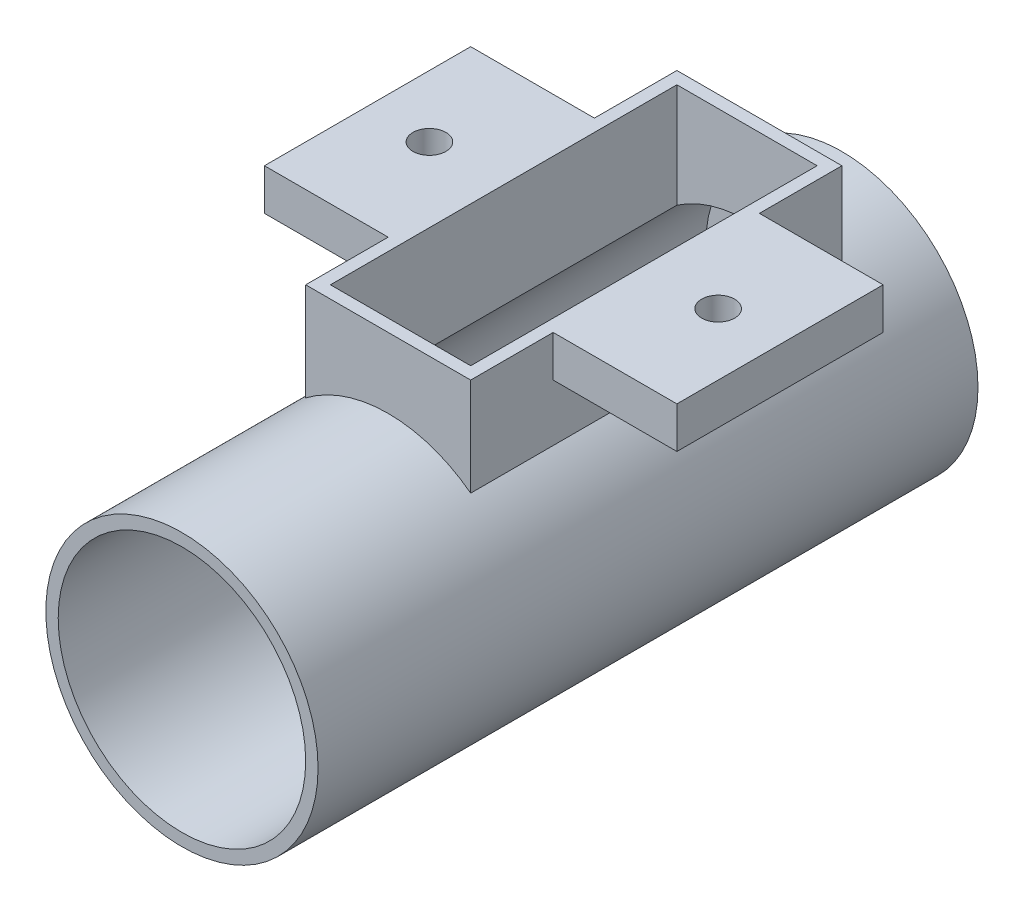
SolidWorks part; units mm, degrees
ref_plane "前视基准面" through (0, 0, 0) normal (0, 0, 1) x (1, 0, 0)
ref_plane "上视基准面" through (0, 0, 0) normal (0, 1, 0) x (1, 0, 0)
ref_plane "右视基准面" through (0, 0, 0) normal (1, 0, 0) x (0, 0, -1)
other "Configuration Table"
sketch "草图1" plane through (0, 0, 0) normal (0, 0, 1) x (1, 0, 0)
  circle A0 centre (0, 0) radius 33
  dimension "D1" = 66
extrude "凸台-拉伸1" add sketch "草图1" along normal blind 160
shell "抽壳1" thickness 3
ref_plane "基准面1" through (0, 33, 0) normal (0, 1, 0) x (1, 0, 0)
ref_plane "基准面2" through (0, 50, 0) normal (0, 1, 0) x (1, 0, 0)
sketch "草图2" plane through (0, 50, 0) normal (0, 1, 0) x (1, 0, 0)
  line L0 (0, 0) -> (0, -160) construction
  line L1 (-20, -20) -> (20, -20)
  line L2 (-20, -20) -> (-20, -110)
  line L3 (-20, -110) -> (20, -110)
  line L4 (20, -20) -> (20, -110)
  line L5 (-20, -20) -> (20, -110) construction
  line L6 (-20, -110) -> (20, -20) construction
  line L7 (-33, -160) -> (33, -160) construction
  line L8 (33, 0) -> (-33, 0) construction
  point P0 (0, -65)
  dimension "D1" = 40
  dimension "D2" = 90
  dimension "D3" = 65
extrude "凸台-拉伸2" add sketch "草图2" against normal up to next
sketch "草图3" plane through (0, 50, 0) normal (0, 1, 0) x (1, 0, 0)
  line L0 (20, -20) -> (-20, -20) construction
  line L1 (-17, -23) -> (17, -23)
  line L2 (-17, -23) -> (-17, -107)
  line L3 (-17, -107) -> (17, -107)
  line L4 (17, -23) -> (17, -107)
  line L5 (-17, -23) -> (17, -107) construction
  line L6 (-17, -107) -> (17, -23) construction
  line L7 (-20, -20) -> (-20, -110) construction
  line L8 (20, -110) -> (20, -20) construction
  line L9 (-20, -110) -> (20, -110) construction
  point P0 (0, -65)
  dimension "D1" = 3
  dimension "D2" = 3
  dimension "D3" = 3
  dimension "D4" = 3
extrude "切除-拉伸1" cut sketch "草图3" against normal blind 60
sketch "草图4" plane through (-20, 0, 0) normal (-1, 0, 0) x (0, 0, 1)
  line L0 (20, 45) -> (110, 45) construction
  line L1 (40, 50) -> (90, 50)
  line L2 (40, 50) -> (40, 40)
  line L3 (40, 40) -> (90, 40)
  line L4 (90, 50) -> (90, 40)
  line L5 (40, 50) -> (90, 40) construction
  line L6 (40, 40) -> (90, 50) construction
  line L9 (20, 26.2488) -> (20, 50) construction
  line L10 (110, 26.2488) -> (110, 50) construction
  line L12 (36.3, 50) -> (-36.3, 50) construction
  point P0 (65, 45)
  dimension "D1" = 50
  dimension "D2" = 10
extrude "凸台-拉伸3" add sketch "草图4" along normal blind 30
sketch "草图5" plane through (0, 50, 0) normal (0, 1, 0) x (1, 0, 0)
  line L0 (-35, -40) -> (-35, -90) construction
  line L1 (-50, -40) -> (-20, -40) construction
  line L2 (-50, -90) -> (-20, -90) construction
  circle A0 centre (-35, -65) radius 4
  dimension "D1" = 8
extrude "切除-拉伸2" cut sketch "草图5" against normal blind 30
sketch "草图6" plane through (20, 0, 0) normal (1, 0, 0) x (0, 0, -1)
  line L0 (-110, 45) -> (-20, 45) construction
  line L1 (-90, 50) -> (-40, 50)
  line L2 (-90, 50) -> (-90, 40)
  line L3 (-90, 40) -> (-40, 40)
  line L4 (-40, 50) -> (-40, 40)
  line L5 (-90, 50) -> (-40, 40) construction
  line L6 (-90, 40) -> (-40, 50) construction
  line L7 (-110, 26.2488) -> (-110, 50) construction
  line L8 (-20, 26.2488) -> (-20, 50) construction
  line L9 (-110, 50) -> (-20, 50) construction
  point P0 (-65, 45)
  dimension "D1" = 10
  dimension "D2" = 50
extrude "凸台-拉伸4" add sketch "草图6" along normal blind 30
sketch "草图7" plane through (0, 50, 0) normal (0, 1, 0) x (1, 0, 0)
  line L0 (35, -40) -> (35, -90) construction
  line L1 (50, -40) -> (20, -40) construction
  line L2 (50, -90) -> (20, -90) construction
  circle A0 centre (35, -65) radius 4
  dimension "D1" = 8
extrude "切除-拉伸3" cut sketch "草图7" against normal blind 30
sketch "草图8" plane through (0, 0, 0) normal (0, 0, -1) x (-1, 0, 0)
  circle A0 centre (0, 0) radius 3.75
  dimension "D1" = 7.5
extrude "切除-拉伸4" cut sketch "草图8" against normal blind 10
